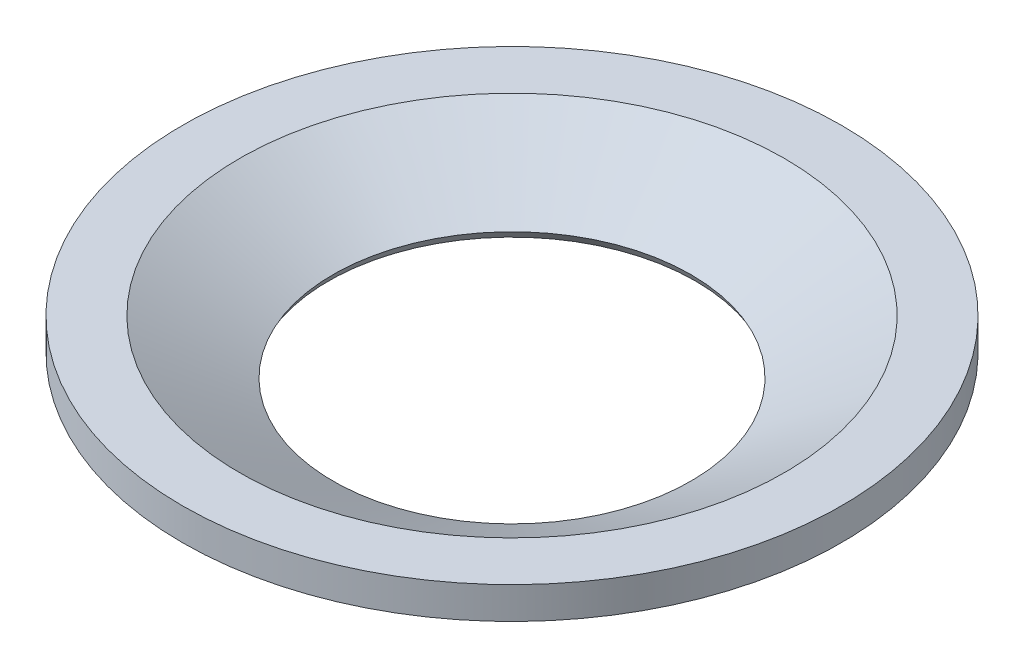
SolidWorks part; units mm, degrees
ref_plane "Front Plane" through (0, 0, 0) normal (0, 0, 1) x (1, 0, 0)
ref_plane "Top Plane" through (0, 0, 0) normal (0, 1, 0) x (1, 0, 0)
ref_plane "Right Plane" through (0, 0, 0) normal (1, 0, 0) x (0, 0, -1)
sketch "Sketch1" plane through (0, 0, 0) normal (0, 0, 1) x (1, 0, 0)
  line L0 (-44.577, 0) -> (-34.925, 5.5726) construction
  line L1 (-44.577, 0) -> (44.577, 0) construction
  line L2 (0, 0) -> (0, 5.5726) construction
  line L3 (-34.925, 5.5726) -> (34.925, 5.5726) construction
  line L4 (-44.577, 0) -> (-44.577, -3.175)
  line L5 (-44.577, 0) -> (-38.227, 0)
  line L6 (-38.227, 0) -> (-25.527, -7.3323)
  point P7 (-28.2318, -5.7707)
  dimension "D1" = 89.154
  dimension "D2" = 30
  dimension "D3" = 69.85
  dimension "D4" = 3.175
  dimension "D5" = 6.35
  dimension "D6" = 150
  dimension "D7" = 19.05
revolve "Revolve-Thin1" add sketch "Sketch1" angle 360 about L2
